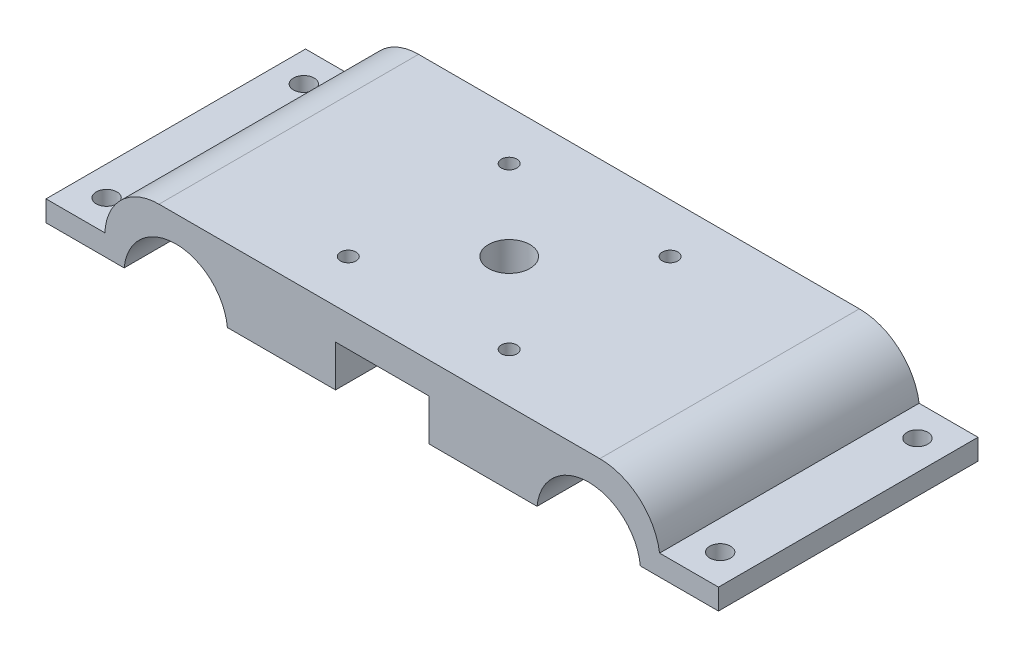
SolidWorks part; units mm, degrees
ref_plane "Piano frontale" through (0, 0, 0) normal (0, 0, 1) x (1, 0, 0)
ref_plane "Piano superiore" through (0, 0, 0) normal (0, 1, 0) x (1, 0, 0)
ref_plane "Piano destro" through (0, 0, 0) normal (1, 0, 0) x (0, 0, -1)
sketch "Schizzo1" plane through (0, 0, 0) normal (0, 0, 1) x (1, 0, 0)
  line L0 (-61.3619, 6.474) -> (38.1881, 6.474) construction
  line L1 (-61.3619, 16.474) -> (38.1881, 16.474) construction
  line L2 (-61.3619, 16.474) -> (-61.3619, -3.526) construction
  line L3 (-61.3619, -3.526) -> (38.1881, -3.526) construction
  line L4 (38.1881, 16.474) -> (38.1881, -3.526) construction
  line L5 (-11.5869, 16.474) -> (-11.5869, -3.526) construction
  line L6 (-41.3619, 6.474) -> (18.1881, 6.474)
  line L8 (38.1881, 6.474) -> (53.1881, 6.474)
  line L9 (53.1881, 6.474) -> (53.1881, 11.474)
  line L10 (53.1881, 11.474) -> (36.8484, 11.474) construction
  line L11 (-61.3619, 6.474) -> (-76.3619, 6.474)
  line L12 (-76.3619, 6.474) -> (-76.3619, 11.474)
  line L13 (-76.3619, 11.474) -> (-60.0221, 11.474) construction
  line L14 (-54.591, 21.474) -> (30.3301, 21.474)
  line L15 (-65.0221, 11.474) -> (-76.3619, 11.474)
  line L16 (53.1881, 11.474) -> (41.8484, 11.474)
  circle A0 centre (-51.3619, 6.474) radius 10 construction
  circle A1 centre (28.1881, 6.474) radius 10 construction
  arc A2 (-61.3619, 6.474) -> (-41.3619, 6.474) centre (-51.3619, 6.474) cw
  arc A3 (18.1881, 6.474) -> (38.1881, 6.474) centre (28.1881, 6.474) cw
  arc A4 (41.8484, 11.474) -> (30.3301, 21.474) centre (30.3301, 9.8405) ccw
  arc A5 (-65.0221, 11.474) -> (-54.591, 21.474) centre (-54.591, 11.0336) cw
  point P26 (-65.0221, 11.474)
  point P27 (41.8484, 11.474)
  dimension "D3" = 20
  dimension "D5" = 10
  dimension "D7" = 10
  dimension "D1" = 99.55
  dimension "D2" = 20
  dimension "D4" = 10
  dimension "D6" = 10
  dimension "D8" = 15
  dimension "D9" = 15
  dimension "D10" = 5
  dimension "D11" = 5
  dimension "D13" = 5
  dimension "D14" = 5
extrude "Estrusione-Estrusione1" add sketch "Schizzo1" along normal blind 50
sketch "Schizzo2" plane through (0, 11.474, 0) normal (0, 1, 0) x (1, 0, 0)
  line L0 (-65.0221, 0) -> (-76.3619, 0) construction
  line L1 (-76.3619, -50) -> (-76.3619, 0) construction
  line L3 (-65.0221, -50) -> (-76.3619, -50) construction
  line L4 (53.1881, -50) -> (53.1881, 0) construction
  line L5 (53.1881, -50) -> (41.8484, -50) construction
  line L6 (53.1881, 0) -> (41.8484, 0) construction
  circle A0 centre (-70.6919, -6) radius 2
  circle A1 centre (-70.6919, -44) radius 2
  circle A2 centre (47.5181, -6) radius 2
  circle A3 centre (47.5181, -44) radius 2
  dimension "D1" = 4
  dimension "D2" = 6
  dimension "D8" = 6
  dimension "D9" = 6
  dimension "D3" = 5.67
  dimension "D4" = 5.67
  dimension "D5" = 6
  dimension "D6" = 5.67
  dimension "D7" = 5.67
extrude "Taglio-Estrusione1" cut sketch "Schizzo2" against normal through all
sketch "Schizzo3" plane through (0, 0, 50) normal (0, 0, 1) x (1, 0, 0)
  line L0 (-41.3619, 6.474) -> (18.1881, 6.474) construction
  line L1 (-20.5869, 6.474) -> (-2.5869, 6.474)
  line L2 (-20.5869, 6.474) -> (-20.5869, 15.474)
  line L3 (-20.5869, 15.474) -> (-2.5869, 15.474)
  line L4 (-2.5869, 6.474) -> (-2.5869, 15.474)
  dimension "D3" = 20.775
  dimension "D1" = 9
  dimension "D2" = 18
extrude "Taglio-Estrusione2" cut sketch "Schizzo3" against normal blind 35
sketch "Schizzo4" plane through (0, 21.474, 0) normal (0, 1, 0) x (1, 0, 0)
  line L0 (-54.591, 0) -> (30.3301, -50) construction
  line L1 (30.3301, 0) -> (-54.591, -50) construction
  line L2 (3.3696, -9.5) -> (3.3696, -40.5) construction
  line L3 (3.3696, -40.5) -> (-27.6304, -40.5) construction
  line L4 (-27.6304, -40.5) -> (-27.6304, -9.5) construction
  line L5 (-27.6304, -9.5) -> (3.3696, -9.5) construction
  circle A0 centre (-12.1304, -25) radius 4
  circle A1 centre (-27.6304, -9.5) radius 1.5
  circle A2 centre (3.3696, -9.5) radius 1.5
  circle A3 centre (3.3696, -40.5) radius 1.5
  circle A4 centre (-27.6304, -40.5) radius 1.5
  dimension "D1" = 8
  dimension "D2" = 3
  dimension "D3" = 31
  dimension "D4" = 15.5
  dimension "D5" = 15.5
extrude "Taglio-Estrusione3" cut sketch "Schizzo4" against normal through all
sketch "Schizzo5" plane through (0, 0, 50) normal (0, 0, 1) x (1, 0, 0)
  line L0 (38.1881, 6.474) -> (53.1881, 6.474) construction
  line L1 (-76.3619, 6.474) -> (53.1881, 6.474)
  line L2 (-76.3619, 6.474) -> (-76.3619, 7.474)
  line L3 (-76.3619, 7.474) -> (53.1881, 7.474)
  line L4 (53.1881, 6.474) -> (53.1881, 7.474)
  line L5 (53.1881, 6.474) -> (53.1881, 11.474) construction
  dimension "D1" = 1
extrude "Taglio-Estrusione4" cut sketch "Schizzo5" against normal through all
